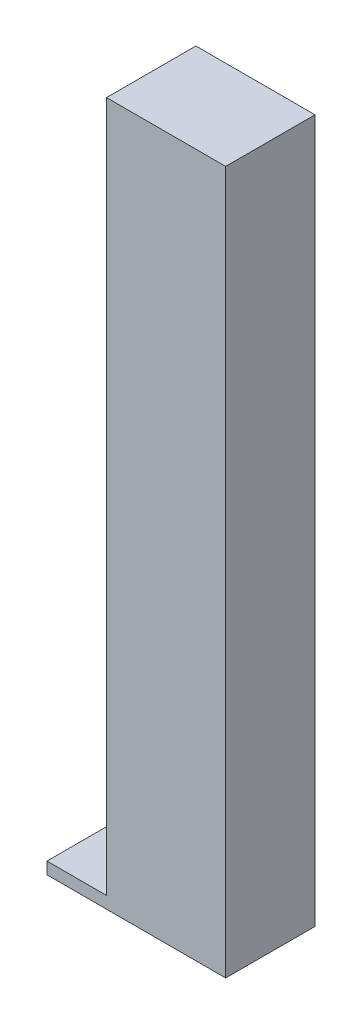
SolidWorks part; units mm, degrees
ref_plane "Front Plane" through (0, 0, 0) normal (0, 0, 1) x (1, 0, 0)
ref_plane "Top Plane" through (0, 0, 0) normal (0, 1, 0) x (1, 0, 0)
ref_plane "Right Plane" through (0, 0, 0) normal (1, 0, 0) x (0, 0, -1)
sketch "Sketch2" plane through (0, 0, 0) normal (0, 1, 0) x (1, 0, 0)
  line L0 (-10, 4.9267) -> (-10, 0.9267)
  line L1 (-10, -10.0733) -> (10, -10.0733)
  line L2 (-10, -10.0733) -> (-10, -6.0733)
  line L3 (-10, 4.9267) -> (10, 4.9267)
  line L4 (10, -10.0733) -> (10, 4.9267)
  line L5 (-10, -6.0733) -> (-7, -6.0733)
  line L6 (-7, -6.0733) -> (-7, -8.0733)
  line L7 (-7, -8.0733) -> (0, -8.0733)
  line L8 (0, -8.0733) -> (0, -9.0733)
  line L9 (0, -9.0733) -> (1, -9.0733)
  line L10 (1, -9.0733) -> (1, -8.0733)
  line L11 (1, -8.0733) -> (8, -8.0733)
  line L12 (8, -8.0733) -> (8, 2.9267)
  line L13 (0, 2.9267) -> (0, 3.9267)
  line L14 (0, 3.9267) -> (1, 3.9267)
  line L15 (1, 3.9267) -> (1, 2.9267)
  line L16 (1, 2.9267) -> (8, 2.9267)
  line L17 (-7, 2.9267) -> (0, 2.9267)
  line L18 (-7, 2.9267) -> (-7, 0.9267)
  line L19 (-7, 0.9267) -> (-10, 0.9267)
  point P0 (0, 0)
  dimension "D1" = 20
  dimension "D2" = 3
  dimension "D3" = 15
  dimension "D4" = 20
  dimension "D5" = 4
  dimension "D6" = 4
extrude "Boss-Extrude1" add sketch "Sketch2" along normal blind 115
ref_plane "Plane1" through (0, 115, 0) normal (0, 1, 0) x (1, 0, 0)
sketch "Sketch3" plane through (0, 115, 0) normal (0, 1, 0) x (1, 0, 0)
  line L1 (-10, -10.0733) -> (10, -10.0733)
  line L2 (-10, -10.0733) -> (-10, 4.9267)
  line L3 (-10, 4.9267) -> (10, 4.9267)
  line L4 (10, -10.0733) -> (10, 4.9267)
extrude "Boss-Extrude2" add sketch "Sketch3" along normal blind 1
ref_plane "Plane2" through (0, 0, 0) normal (0, -1, 0) x (-1, 0, 0)
sketch "Sketch7" plane through (0, 0, 0) normal (0, -1, 0) x (-1, 0, 0)
  line L1 (-10, 4.9267) -> (20, 4.9267)
  line L2 (-10, 4.9267) -> (-10, -10.0733)
  line L3 (-10, -10.0733) -> (20, -10.0733)
  line L4 (20, 4.9267) -> (20, -10.0733)
extrude "Boss-Extrude5" add sketch "Sketch7" along normal blind 2
ref_plane "Plane3" through (0, 0, 0) normal (0, 1, 0) x (1, 0, 0)
sketch "Sketch8" plane through (0, 0, 0) normal (0, 1, 0) x (1, 0, 0)
  line L0 (-10, 0.9267) -> (-10, -2.5733)
  line L1 (-10, -2.5733) -> (-10, -6.0733)
sketch "Sketch9" plane through (0, 0, 0) normal (0, 1, 0) x (1, 0, 0)
  line L0 (-11.4601, 4.9267) -> (-20, 4.9267)
  line L1 (-20, 4.9267) -> (-10, 4.9267) construction
  line L2 (-11.4601, 4.9267) -> (-11.4601, -2.5733)
  line L3 (-11.4601, -2.5733) -> (-11.4601, -10.0733)
  line L4 (-10, -10.0733) -> (-20, -10.0733) construction
  line L5 (-20, 4.9267) -> (-20, -10.0733)
  line L6 (-20, -10.0733) -> (-11.4601, -10.0733)
  line L7 (-11.4601, -2.5733) -> (-12.4601, -2.5733) construction
  line L8 (-12.4601, -2.5733) -> (-13.4601, -2.5733) construction
  line L9 (-13.4601, -2.5733) -> (-14.4601, -2.5733) construction
  line L10 (-14.4601, -2.5733) -> (-15.4601, -2.5733) construction
  line L11 (-15.4601, -2.5733) -> (-16.4601, -2.5733) construction
  line L12 (-16.4601, -2.5733) -> (-20, -2.5733) construction
  line L13 (-12.4601, -2.5733) -> (-12.4601, 4.9267)
  line L14 (-12.4601, -2.5733) -> (-12.4601, -10.0733)
  line L15 (-13.4601, -2.5733) -> (-13.4601, -10.0733)
  line L16 (-13.4601, -2.5733) -> (-13.4601, 4.9267)
  line L17 (-14.4601, -2.5733) -> (-14.4601, -10.0733)
  line L18 (-14.4601, -2.5733) -> (-14.4601, 4.9267)
  line L19 (-15.4601, -2.5733) -> (-15.4601, 4.9267) construction
  line L20 (-15.4601, -2.5733) -> (-15.4601, -10.0733) construction
  line L21 (-16.4601, -2.5733) -> (-16.4601, -10.0733)
  line L22 (-16.4601, -2.5733) -> (-16.4601, 4.9267)
  line L23 (-18.23, -2.5733) -> (-18.23, -10.0733)
  line L24 (-18.23, -2.5733) -> (-18.23, 4.9267)
  line L25 (-17.3492, -2.5733) -> (-17.3492, -10.0733)
  line L26 (-17.3492, -2.5733) -> (-17.3492, 4.9267)
sketch "Sketch10" plane through (0, 0, 0) normal (1, 0, 0) x (0, 0, -1)
  line L0 (-2.5796, 115) -> (-2.5796, 1.3869)
  line L1 (55, 115) -> (-55, 115) construction
